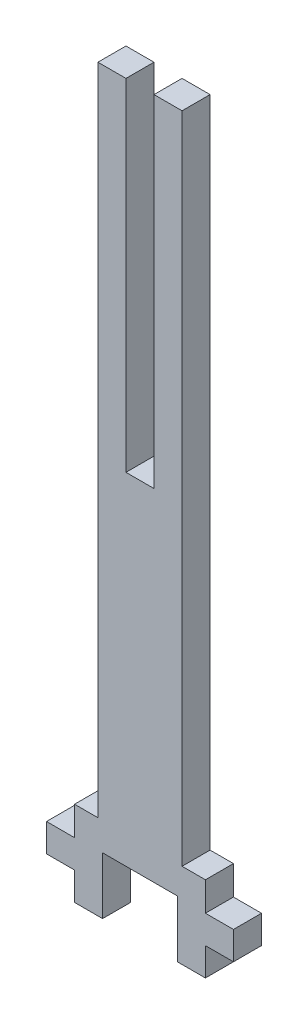
SolidWorks part; units mm, degrees
ref_plane "Front Plane" through (0, 0, 0) normal (0, 0, 1) x (1, 0, 0)
ref_plane "Top Plane" through (0, 0, 0) normal (0, 1, 0) x (1, 0, 0)
ref_plane "Right Plane" through (0, 0, 0) normal (1, 0, 0) x (0, 0, -1)
sketch "스케치1" plane through (0, 0, 0) normal (0, 0, 1) x (1, 0, 0)
  line L0 (0, 0) -> (0, -33.446) construction
  line L1 (-7, -39.546) -> (7, -39.546) construction
  line L2 (-7, -39.546) -> (-7, 39.546) construction
  line L3 (-7, 39.546) -> (7, 39.546) construction
  line L4 (7, -39.546) -> (7, 39.546) construction
  line L5 (-7, -39.546) -> (7, 39.546) construction
  line L6 (-7, 39.546) -> (7, -39.546) construction
  line L7 (-4, -39.546) -> (4, -39.546) construction
  line L8 (-4, -39.546) -> (-4, -33.446)
  line L9 (-4, -33.446) -> (4, -33.446)
  line L10 (4, -39.546) -> (4, -33.446)
  line L11 (-4, -39.546) -> (4, -33.446) construction
  line L12 (-4, -33.446) -> (4, -39.546) construction
  line L13 (4.5, -30.446) -> (-4.5, -30.446) construction
  line L14 (7, -30.446) -> (4.5, -30.446)
  line L15 (7, -30.446) -> (7, 39.546) construction
  line L16 (7, 39.546) -> (4.5, 39.546) construction
  line L17 (4.5, -30.446) -> (4.5, 39.546) construction
  line L18 (7, -30.446) -> (4.5, 39.546) construction
  line L19 (7, 39.546) -> (4.5, -30.446) construction
  line L20 (-4.5, 39.546) -> (-7, 39.546) construction
  line L21 (-4.5, 39.546) -> (-4.5, -30.446) construction
  line L22 (-4.5, -30.446) -> (-7, -30.446)
  line L23 (-7, 39.546) -> (-7, -30.446) construction
  line L24 (-4.5, 39.546) -> (-7, -30.446) construction
  line L25 (-4.5, -30.446) -> (-7, 39.546) construction
  line L26 (4, -39.546) -> (7, -39.546)
  line L27 (-1.5, 30.446) -> (1.5, 30.446) construction
  line L28 (-1.5, 30.446) -> (-1.5, -30.446) construction
  line L29 (-1.5, -30.446) -> (1.5, -30.446) construction
  line L30 (1.5, 30.446) -> (1.5, -30.446) construction
  line L31 (-1.5, 30.446) -> (1.5, -30.446) construction
  line L32 (-1.5, -30.446) -> (1.5, 30.446) construction
  line L33 (7, -39.546) -> (7, -30.446)
  line L34 (-7, -30.446) -> (-7, -39.546)
  line L35 (-7, -39.546) -> (-4, -39.546)
  line L36 (-4.5, 39.546) -> (-7, 39.546) construction
  line L37 (-7, 39.546) -> (-7, -39.546)
  line L38 (4.5, 39.546) -> (7, 39.546) construction
  line L39 (-4.5, -30.446) -> (-4.5, 39.546)
  line L40 (4.5, 39.546) -> (4.5, -30.446)
  line L41 (-4.5, 39.546) -> (4.5, 39.546)
  point P0 (0, 0)
  point P10 (0, -36.496)
  point P16 (5.75, 4.55)
  point P20 (-5.75, 4.55)
  dimension "D1" = 69.992
  dimension "D2" = 3
  dimension "D3" = 8
  dimension "D4" = 6.1
  dimension "D5" = 3
  dimension "D6" = 3
  dimension "D7" = 3
extrude "보스-돌출1" add sketch "스케치1" along normal blind 3 contours L41 L39 L22 L34 L35 L8 L9 L10 L26 L33 L14 L40
sketch "스케치2" plane through (0, 0, 3) normal (0, 0, 1) x (1, 0, 0)
  line L0 (0, 39.546) -> (0, -33.446) construction
  line L1 (-4.5, 39.546) -> (4.5, 39.546) construction
  line L2 (-4, -33.446) -> (4, -33.446) construction
  line L4 (-1.5, 39.546) -> (1.5, 39.546)
  line L5 (-1.5, 39.546) -> (-1.5, 3.05)
  line L6 (-1.5, 3.05) -> (1.5, 3.05)
  line L7 (1.5, 39.546) -> (1.5, 3.05)
  line L8 (-1.5, 39.546) -> (1.5, 3.05) construction
  line L9 (-1.5, 3.05) -> (1.5, 39.546) construction
  point P6 (0, 3.05)
  point P7 (0, 21.298)
  dimension "D1" = 3
extrude "컷-돌출1" cut sketch "스케치2" against normal up to surface (3 mm away) up to face at (0, -22.314, 0)
sketch "스케치3" plane through (0, 0, 3) normal (0, 0, 1) x (1, 0, 0)
  line L0 (-7, -39.546) -> (-4, -39.546) construction
  line L1 (-7, -36.546) -> (-10, -36.546)
  line L2 (-7, -36.546) -> (-7, -33.546)
  line L3 (-7, -33.546) -> (-10, -33.546)
  line L4 (-10, -36.546) -> (-10, -33.546)
  line L5 (-7, -36.546) -> (-10, -33.546) construction
  line L6 (-7, -33.546) -> (-10, -36.546) construction
  line L7 (7, -36.546) -> (10, -36.546)
  line L8 (7, -36.546) -> (7, -33.546)
  line L9 (7, -33.546) -> (10, -33.546)
  line L10 (10, -36.546) -> (10, -33.546)
  line L11 (7, -36.546) -> (10, -33.546) construction
  line L12 (7, -33.546) -> (10, -36.546) construction
  line L13 (7, -39.546) -> (7, -30.446) construction
  line L14 (-7, -30.446) -> (-7, -39.546) construction
  point P4 (-8.5, -35.046)
  point P10 (8.5, -35.046)
  point P11 (0, 0)
  point P13 (0, 0)
  point P14 (-8.4301, -34.2318)
  point P15 (8.4361, -34.2318)
  point P19 (0, 0)
  point P22 (0, 0)
  dimension "D1" = 3
  dimension "D2" = 3
  dimension "D3" = 3
  dimension "D4" = 3
  dimension "D5" = 3
  dimension "D6" = 3
extrude "보스-돌출2" add sketch "스케치3" against normal blind 3
